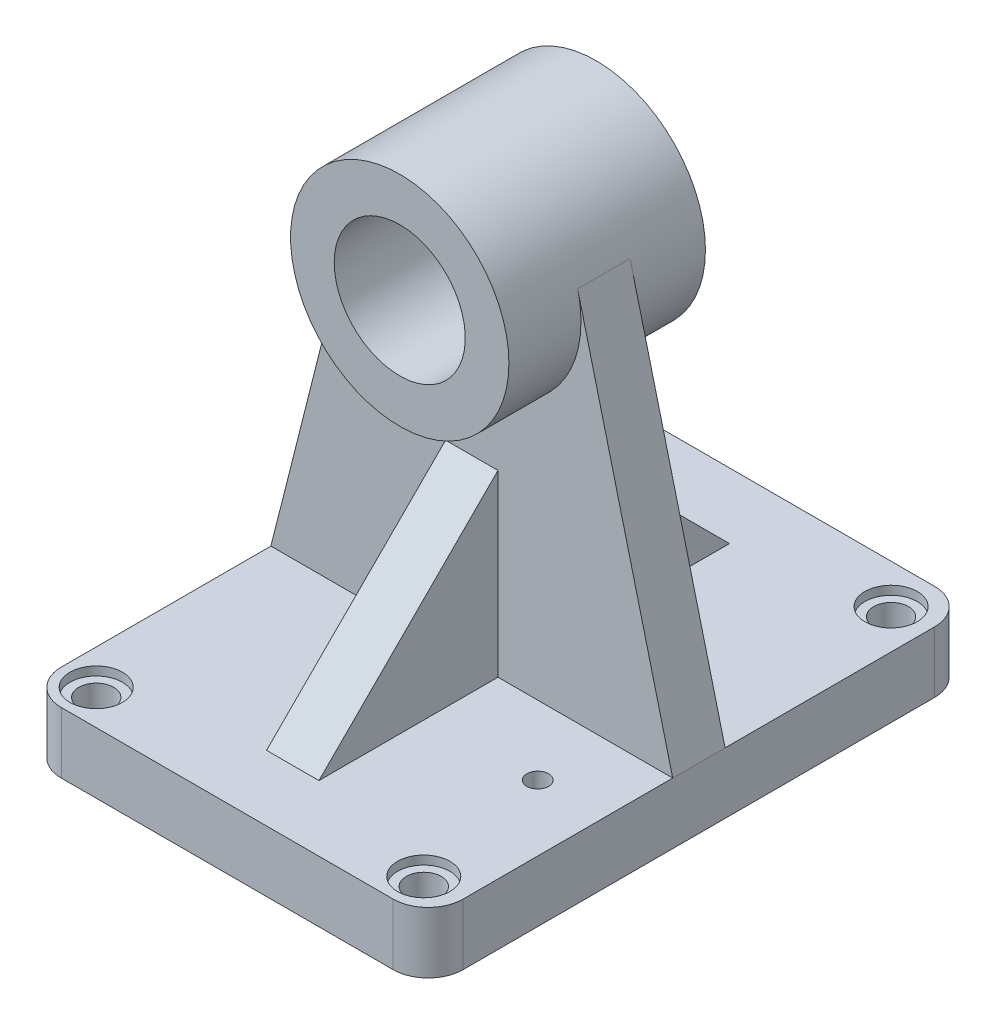
SolidWorks part; units mm, degrees
ref_plane "정면" through (0, 0, 0) normal (0, 0, 1) x (1, 0, 0)
ref_plane "윗면" through (0, 0, 0) normal (0, 1, 0) x (1, 0, 0)
ref_plane "우측면" through (0, 0, 0) normal (1, 0, 0) x (0, 0, -1)
sketch "스케치1" plane through (0, 0, 0) normal (0, 0, 1) x (1, 0, 0)
  circle A0 centre (0, 0) radius 15
  circle A1 centre (0, 0) radius 25
  dimension "D1" = 50
  dimension "D2" = 30
extrude "보스-돌출1" add sketch "스케치1" along normal mid plane 45
sketch "스케치2" plane through (0, 0, 0) normal (0, 0, 1) x (1, 0, 0)
  line L1 (-46, -80) -> (46, -80)
  line L2 (-46, -80) -> (-46, -94)
  line L3 (-46, -94) -> (46, -94)
  line L4 (46, -80) -> (46, -94)
  point P4 (0, -80)
  dimension "D1" = 92
  dimension "D2" = 14
  dimension "D3" = 80
extrude "보스-돌출2" add sketch "스케치2" against normal mid plane 124 separate body contours L1 L4 L3 L2
sketch "스케치3" plane through (0, 0, 0) normal (0, 0, 1) x (1, 0, 0)
  line L0 (-24.2382, 6.1245) -> (-46, -80)
  line L1 (24.2382, 6.1245) -> (46, -80)
  line L2 (-46, -80) -> (46, -80)
  circle A0 centre (0, 0) radius 25 construction
  arc A1 (-24.2382, 6.1245) -> (24.2382, 6.1245) centre (0, 0) ccw
extrude "보스-돌출3" add sketch "스케치3" along normal mid plane 12
sketch "스케치4" plane through (0, 0, 0) normal (1, 0, 0) x (0, 0, -1)
  line L0 (-6, -39) -> (-47, -80)
  line L6 (-6, -80) -> (-6, 6.1245) construction
  line L7 (-6, -80) -> (-62, -80) construction
  dimension "D1" = 15
  dimension "D2" = 45
rib "보강대1" sketch "스케치4" sketch "스케치4" thickness 12 extrusion direction parallel to sketch draft on no parameters "D1"=12
mirror "대칭 복사1" about plane through (0, 0, 0) normal (0, 0, 1) of "보강대1"
fillet "필렛1" radius 8 4 edges at (-46, -87, -62) (46, -87, -62) (46, -87, 62) (-46, -87, 62)
hole_wizard "M5 소켓 머리 캡 나사용 카운터보어1" positions "3D스케치1" profile "스케치6" counterbore size "M5" standard "KS" end condition through all
sketch3d "3D스케치1"
  line L0 (-38, -80, 54) -> (-38, -94, 54) construction
  point P0 (-38, -80, 54)
sketch "스케치6" plane through (-38, -80, 54) normal (1, 0, 0) x (0, 0, 1)
  line L0 (0, 0) -> (0, 14)
  line L1 (0, 14) -> (4, 14)
  line L3 (4, 14) -> (4, 2)
  line L4 (4, 2) -> (6, 2)
  line L5 (6, 2) -> (6, 0)
  line L7 (6, 0) -> (0, 0)
  line L11 (0, -6.35) -> (0, 107.95) construction
  dimension "관통 구멍 지름" = 8
  dimension "관통 구멍 깊이" = 14
  dimension "카운터보어 지름" = 12
  dimension "카운터보어 깊이" = 2
hole_wizard "M6 나사 구멍1" positions "3D스케치2" profile "스케치8" tap size "M6" standard "KS" end condition through all
sketch3d "3D스케치2"
  point P0 (30.9432, -80, 21.844)
sketch "스케치8" plane through (30.9432, -80, 21.844) normal (1, 0, 0) x (0, 0, 1)
  line L0 (0, 0) -> (0, 14)
  line L1 (0, 14) -> (2.5, 14)
  line L2 (2.5, 14) -> (2.5, 0)
  line L5 (2.5, 0) -> (0, 0)
  line L11 (0, -6.35) -> (0, 107.95) construction
  dimension "관통 탭 드릴 지름" = 5
  dimension "관통 탭 드릴 깊이" = 14
cosmetic thread "구멍 나사산1" parameters "D2"=6
pattern_linear "선형 패턴7" count 2 spacing 75 along (1, 0, 0) count 2 spacing 107 along (0, 0, -1) of "M5 소켓 머리 캡 나사용 카운터보어1"
